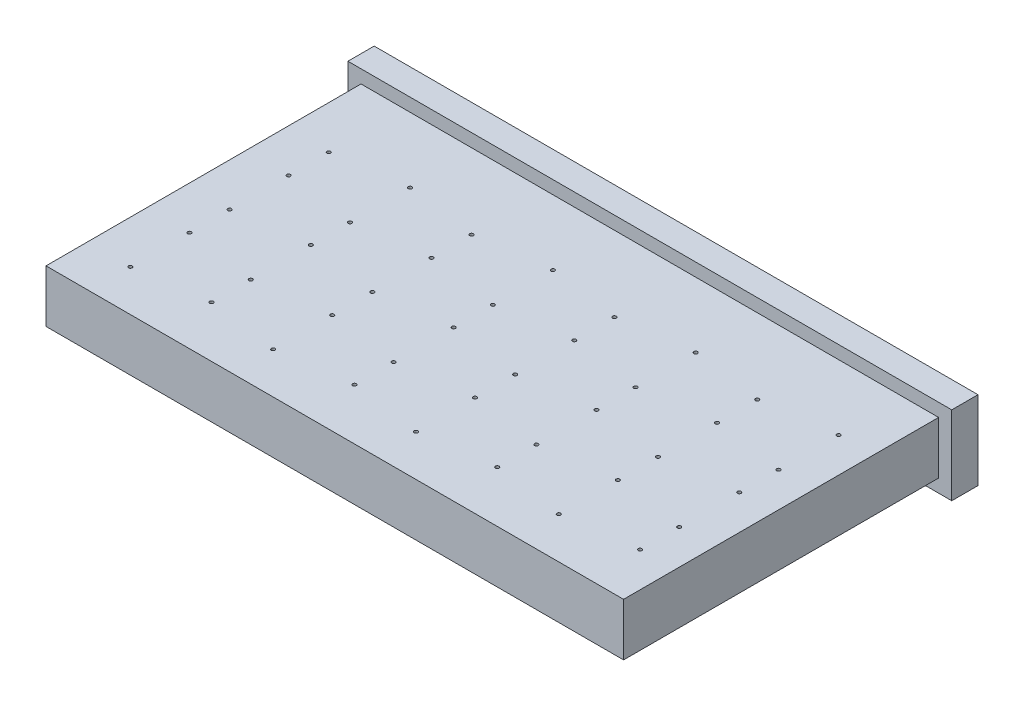
SolidWorks part; units mm, degrees
material "ABS"
ref_plane "X-Y Datum" through (0, 0, 0) normal (0, 0, 1) x (1, 0, 0)
ref_plane "X-Z Datum" through (0, 0, 0) normal (0, 1, 0) x (1, 0, 0)
ref_plane "Y-Z Datum" through (0, 0, 0) normal (1, 0, 0) x (0, 0, -1)
sketch "Sketch1" plane through (0, 0, 0) normal (0, 0, 1) x (1, 0, 0)
  line L1 (-146.05, -19.05) -> (146.05, -19.05)
  line L2 (-146.05, -19.05) -> (-146.05, 19.05)
  line L3 (-146.05, 19.05) -> (146.05, 19.05)
  line L4 (146.05, -19.05) -> (146.05, 19.05)
  line L5 (-146.05, -19.05) -> (146.05, 19.05) construction
  line L6 (-146.05, 19.05) -> (146.05, -19.05) construction
  point P0 (0, 0)
  dimension "D1" = 38.1
  dimension "D2" = 292.1
extrude "Boss-Extrude1" add sketch "Sketch1" along normal blind 12.7
sketch "Sketch2" plane through (0, 0, 12.7) normal (0, 0, 1) x (1, 0, 0)
  line L0 (-146.05, 0) -> (146.05, 0) construction
  line L1 (146.05, -19.05) -> (146.05, 19.05) construction
  line L3 (-139.7, -12.7) -> (139.7, -12.7)
  line L4 (-139.7, -12.7) -> (-139.7, 12.7)
  line L5 (-139.7, 12.7) -> (139.7, 12.7)
  line L6 (139.7, -12.7) -> (139.7, 12.7)
  line L7 (-139.7, -12.7) -> (139.7, 12.7) construction
  line L8 (-139.7, 12.7) -> (139.7, -12.7) construction
  point P0 (0, 0)
  point P6 (0, 0)
  dimension "D2" = 279.4
  dimension "D1" = 25.4
extrude "Boss-Extrude2" add sketch "Sketch2" along normal blind 152.4
sketch "Sketch3" plane through (0, 12.7, 0) normal (0, 1, 0) x (1, 0, 0)
  line L0 (139.7, -88.9) -> (-139.7, -88.9) construction
  line L1 (139.7, -165.1) -> (139.7, -12.7) construction
  line L2 (-139.7, -165.1) -> (-139.7, -12.7) construction
  line L4 (139.7, -19.05) -> (-139.7, -19.05)
  line L5 (139.7, -19.05) -> (139.7, -158.75)
  line L6 (139.7, -158.75) -> (-139.7, -158.75)
  line L7 (-139.7, -19.05) -> (-139.7, -158.75)
  line L8 (139.7, -19.05) -> (-139.7, -158.75) construction
  line L9 (139.7, -158.75) -> (-139.7, -19.05) construction
  circle A0 centre (130.81, -149.86) radius 1.27
  point P6 (0, -88.9)
  dimension "D4" = 2.54
  dimension "D1" = 139.7
  dimension "D2" = 279.4
  dimension "D3" = 8.89
  dimension "D5" = 8.89
sketch "Sketch4" plane through (0, -12.7, 0) normal (0, -1, 0) x (1, 0, 0)
  circle A0 centre (-118.8948, 145.1079) radius 0.875 construction
  circle A1 centre (-118.8948, 145.1079) radius 0.875
  circle A2 centre (88.3692, 49.1061) radius 0.875 construction
  circle A3 centre (122.8692, 44.2911) radius 0.875 construction
  circle A4 centre (122.8692, 73.351) radius 0.875 construction
  circle A5 centre (88.3692, 68.5361) radius 0.875 construction
  circle A6 centre (88.3692, 97.107) radius 0.875 construction
  circle A7 centre (122.8692, 92.2921) radius 0.875 construction
  circle A8 centre (122.8692, 121.357) radius 0.875 construction
  circle A9 centre (122.8692, 140.293) radius 0.875 construction
  circle A10 centre (88.3692, 116.5421) radius 0.875 construction
  circle A11 centre (88.3692, 145.1079) radius 0.875 construction
  circle A12 centre (53.7812, 140.293) radius 0.875 construction
  circle A13 centre (53.7812, 121.357) radius 0.875 construction
  circle A14 centre (53.7812, 92.2921) radius 0.875 construction
  circle A15 centre (53.7812, 73.351) radius 0.875 construction
  circle A16 centre (53.7812, 44.2911) radius 0.875 construction
  circle A17 centre (19.2812, 68.5361) radius 0.875 construction
  circle A18 centre (19.2812, 97.107) radius 0.875 construction
  circle A19 centre (19.2812, 116.5421) radius 0.875 construction
  circle A20 centre (19.2812, 145.1079) radius 0.875 construction
  circle A21 centre (-15.3068, 140.293) radius 0.875 construction
  circle A22 centre (-15.3068, 92.2921) radius 0.875 construction
  circle A23 centre (-49.8068, 97.107) radius 0.875 construction
  circle A24 centre (19.2812, 49.1061) radius 0.875 construction
  circle A25 centre (-15.3068, 44.2911) radius 0.875 construction
  circle A26 centre (-15.3068, 73.351) radius 0.875 construction
  circle A27 centre (-49.8068, 68.5361) radius 0.875 construction
  circle A28 centre (-49.8068, 49.1061) radius 0.875 construction
  circle A29 centre (-49.8068, 116.5421) radius 0.875 construction
  circle A30 centre (-49.8068, 145.1079) radius 0.875 construction
  circle A31 centre (-84.3948, 121.357) radius 0.875 construction
  circle A32 centre (-84.3948, 92.2921) radius 0.875 construction
  circle A33 centre (-84.3948, 73.351) radius 0.875 construction
  circle A34 centre (-84.3948, 44.2911) radius 0.875 construction
  circle A35 centre (-118.8948, 49.1061) radius 0.875 construction
  circle A36 centre (-118.8948, 68.5361) radius 0.875 construction
  circle A37 centre (-118.8948, 97.107) radius 0.875 construction
  circle A38 centre (-118.8948, 116.5421) radius 0.875 construction
  circle A39 centre (-84.3948, 140.293) radius 0.875 construction
  circle A40 centre (88.3692, 49.1061) radius 0.875
  circle A41 centre (122.8692, 44.2911) radius 0.875
  circle A42 centre (122.8692, 73.351) radius 0.875
  circle A43 centre (88.3692, 68.5361) radius 0.875
  circle A44 centre (88.3692, 97.107) radius 0.875
  circle A45 centre (122.8692, 92.2921) radius 0.875
  circle A46 centre (122.8692, 121.357) radius 0.875
  circle A47 centre (122.8692, 140.293) radius 0.875
  circle A48 centre (88.3692, 116.5421) radius 0.875
  circle A49 centre (88.3692, 145.1079) radius 0.875
  circle A50 centre (53.7812, 140.293) radius 0.875
  circle A51 centre (53.7812, 121.357) radius 0.875
  circle A52 centre (53.7812, 92.2921) radius 0.875
  circle A53 centre (53.7812, 73.351) radius 0.875
  circle A54 centre (53.7812, 44.2911) radius 0.875
  circle A55 centre (19.2812, 68.5361) radius 0.875
  circle A56 centre (19.2812, 97.107) radius 0.875
  circle A57 centre (19.2812, 116.5421) radius 0.875
  circle A58 centre (19.2812, 145.1079) radius 0.875
  circle A59 centre (-15.3068, 140.293) radius 0.875
  circle A60 centre (-15.3068, 92.2921) radius 0.875
  circle A61 centre (-49.8068, 97.107) radius 0.875
  circle A62 centre (19.2812, 49.1061) radius 0.875
  circle A63 centre (-15.3068, 44.2911) radius 0.875
  circle A64 centre (-15.3068, 73.351) radius 0.875
  circle A65 centre (-49.8068, 68.5361) radius 0.875
  circle A66 centre (-49.8068, 49.1061) radius 0.875
  circle A67 centre (-49.8068, 116.5421) radius 0.875
  circle A68 centre (-49.8068, 145.1079) radius 0.875
  circle A69 centre (-118.8948, 145.1079) radius 0.875
  circle A70 centre (-84.3948, 121.357) radius 0.875
  circle A71 centre (-84.3948, 92.2921) radius 0.875
  circle A72 centre (-84.3948, 73.351) radius 0.875
  circle A73 centre (-84.3948, 44.2911) radius 0.875
  circle A74 centre (-118.8948, 49.1061) radius 0.875
  circle A75 centre (-118.8948, 68.5361) radius 0.875
  circle A76 centre (-118.8948, 97.107) radius 0.875
  circle A77 centre (-118.8948, 116.5421) radius 0.875
  circle A78 centre (-84.3948, 140.293) radius 0.875
  circle A79 centre (-15.3068, 121.357) radius 0.875 construction
  circle A80 centre (-15.3068, 121.357) radius 0.875
extrude "Cut-Extrude1" cut sketch "Sketch4" against normal through all contours A77 | A75 | A72 | A74 | A73 | A65 | A67 | A68 | A63 | A64 | A57 | A58 | A51 | A45 | A43 | A40 | A41 | A42 | A44 | A1 | A78 | A70 | A76 | A71 | A66 | A61 | A59 | A60 | A62 | A55 | A56 | A50 | A49 | A47 | A46 | A48 | A54 | A52 | A53 | A80
